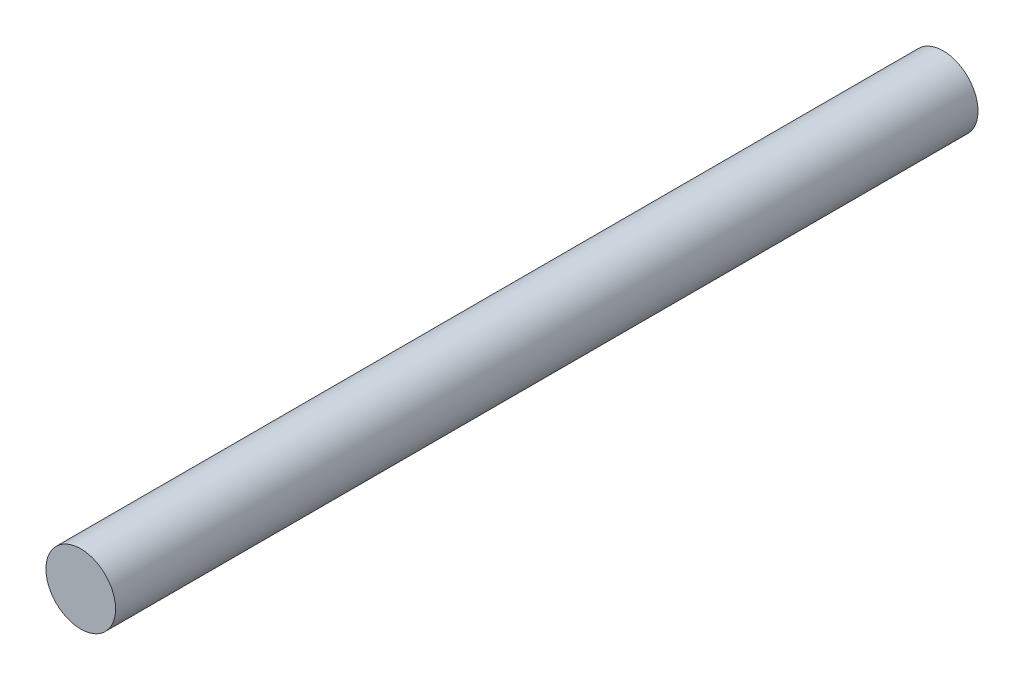
SolidWorks part; units mm, degrees
ref_plane "Alzado" through (0, 0, 0) normal (0, 0, 1) x (1, 0, 0)
ref_plane "Planta" through (0, 0, 0) normal (0, 1, 0) x (1, 0, 0)
ref_plane "Vista lateral" through (0, 0, 0) normal (1, 0, 0) x (0, 0, -1)
sketch "Croquis1" plane through (0, 0, 0) normal (0, 0, 1) x (1, 0, 0)
  circle A0 centre (0, 0) radius 2.95
extrude "Saliente-Extruir1" add sketch "Croquis1" along normal blind 73.1
